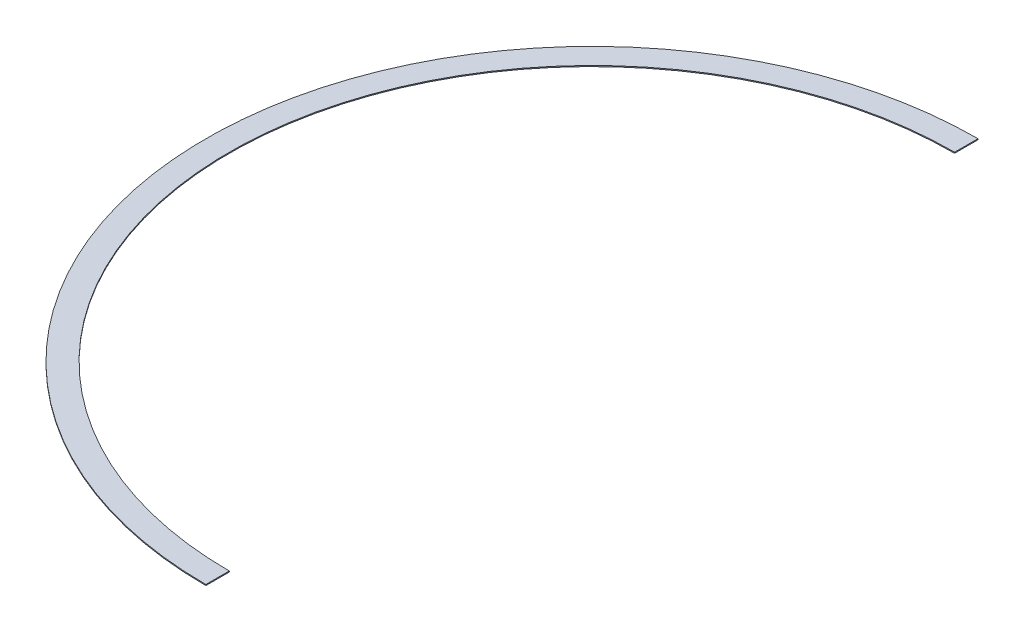
SolidWorks part; units mm, degrees
ref_plane "Front" through (0, 0, 0) normal (0, 0, 1) x (1, 0, 0)
ref_plane "Top" through (0, 0, 0) normal (0, 1, 0) x (1, 0, 0)
ref_plane "Right" through (0, 0, 0) normal (1, 0, 0) x (0, 0, -1)
sketch "Sketch1" plane through (0, 0, 0) normal (0, 1, 0) x (1, 0, 0)
  line L0 (0, 304.8) -> (0, -304.8) construction
  line L1 (0, 0) -> (-304.8, 0) construction
  arc A0 (0, 304.8) -> (0, -304.8) centre (0, 0) ccw
  dimension "D1" = 609.6
extrude "Extrude-Thin1" add sketch "Sketch1" along normal blind 0.7937 thin thin type mid plane wall 19.05
